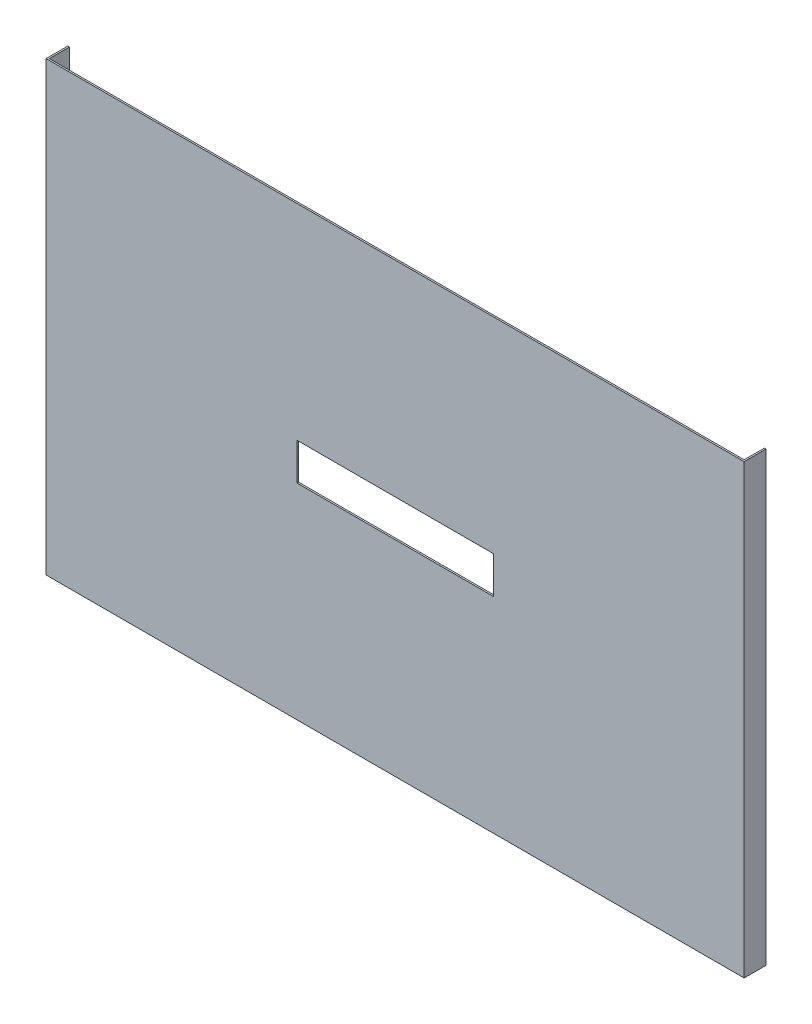
SolidWorks part; units mm, degrees
ref_plane "Front Plane" through (0, 0, 0) normal (0, 0, 1) x (1, 0, 0)
ref_plane "Top Plane" through (0, 0, 0) normal (0, 1, 0) x (1, 0, 0)
ref_plane "Right Plane" through (0, 0, 0) normal (1, 0, 0) x (0, 0, -1)
other "Configuration Table"
sketch "Sketch1" plane through (0, 0, 0) normal (0, 1, 0) x (1, 0, 0)
  line L0 (30, -40) -> (30, -20)
  line L1 (30, -20) -> (31.5, -20)
  line L2 (31.5, -20) -> (31.5, -38.5)
  line L3 (31.5, -38.5) -> (668.5, -38.5)
  line L4 (668.5, -38.5) -> (668.5, -20)
  line L5 (668.5, -20) -> (670, -20)
  line L6 (670, -20) -> (670, -40)
  line L7 (670, -40) -> (30, -40)
extrude "TOPPING_klape_kat2_kapak_1" add sketch "Sketch1" along normal blind 410 from offset 1150 separate body
sketch "Sketch2" plane through (0, 0, 0) normal (0, 0, 1) x (1, 0, 0)
  line L1 (260, 1338) -> (440, 1338)
  line L2 (260, 1338) -> (260, 1372)
  line L3 (260, 1372) -> (440, 1372)
  line L4 (440, 1338) -> (440, 1372)
extrude "TOPPING_klape_kat2_kapak_2" cut sketch "Sketch2" along normal blind 14 from offset 27
